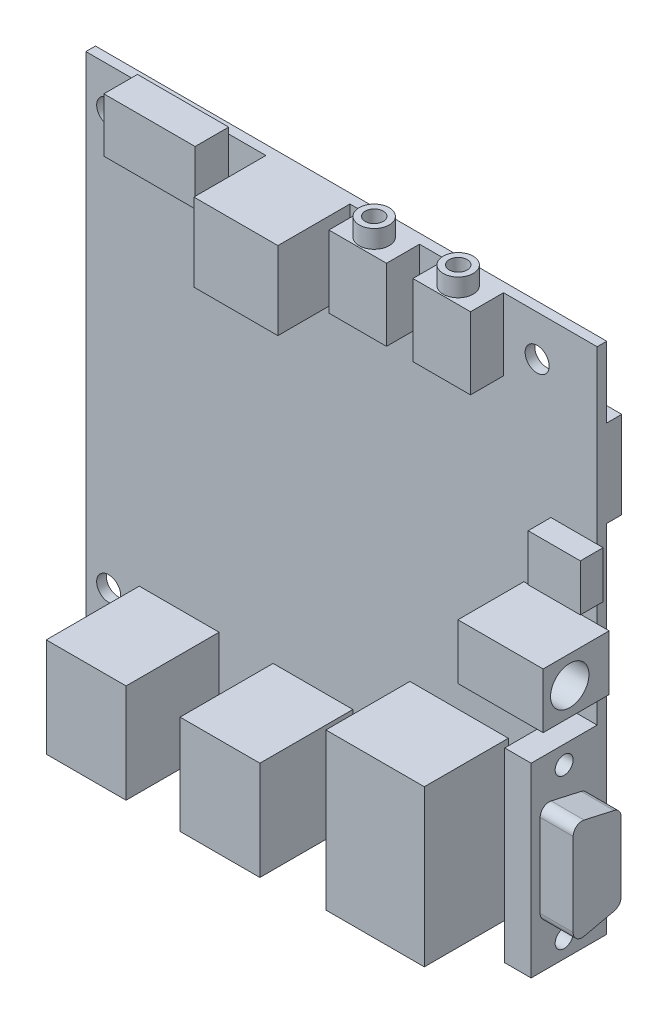
SolidWorks part; units mm, degrees
ref_plane "Piano frontale" through (0, 0, 0) normal (0, 0, 1) x (1, 0, 0)
ref_plane "Piano superiore" through (0, 0, 0) normal (0, 1, 0) x (1, 0, 0)
ref_plane "Piano destro" through (0, 0, 0) normal (1, 0, 0) x (0, 0, -1)
sketch "Schizzo1" plane through (0, 0, 0) normal (0, 0, 1) x (1, 0, 0)
  line L1 (42.6, -42.8) -> (-42.6, -42.8)
  line L2 (42.6, -42.8) -> (42.6, 42.8)
  line L3 (42.6, 42.8) -> (-42.6, 42.8)
  line L4 (-42.6, -42.8) -> (-42.6, 42.8)
  line L5 (42.6, -42.8) -> (-42.6, 42.8) construction
  line L6 (42.6, 42.8) -> (-42.6, -42.8) construction
  circle A0 centre (-38.8, 36) radius 2
  circle A1 centre (32.6, 36) radius 2
  circle A2 centre (-38.8, -32.8) radius 2
  circle A3 centre (32.6, -32.8) radius 2
  point P0 (0, 0)
  dimension "D5" = 4
  dimension "D6" = 4
  dimension "D9" = 4
  dimension "D12" = 4
  dimension "D1" = 85.2
  dimension "D2" = 85.6
  dimension "D3" = 6.8
  dimension "D4" = 3.8
  dimension "D7" = 10
  dimension "D8" = 6.8
  dimension "D10" = 10
  dimension "D11" = 3.8
  dimension "D13" = 10
  dimension "D14" = 10
extrude "Estrusione-Estrusione1" add sketch "Schizzo1" along normal blind 1.6
sketch "Schizzo2" plane through (0, 0, 1.6) normal (0, 0, 1) x (1, 0, 0)
  text T0 "beagleboard xm"
sketch "Schizzo3" plane through (0, 0, 1.6) normal (0, 0, 1) x (1, 0, 0)
  line L0 (-42.6, 42.8) -> (-42.6, -42.8) construction
  line L1 (-34, 43.8) -> (-18.8, 43.8)
  line L2 (-34, 43.8) -> (-34, 34.8)
  line L3 (-34, 34.8) -> (-18.8, 34.8)
  line L4 (-18.8, 43.8) -> (-18.8, 34.8)
  line L5 (42.6, 42.8) -> (-42.6, 42.8) construction
  dimension "D1" = 8.6
  dimension "D2" = 15.2
  dimension "D3" = 9
  dimension "D4" = 1
extrude "Estrusione-Estrusione2" add sketch "Schizzo3" along normal blind 5.6
sketch "Schizzo4" plane through (0, 0, 1.6) normal (0, 0, 1) x (1, 0, 0)
  line L0 (42.6, 42.8) -> (-18.8, 42.8) construction
  line L1 (-12.6, 42.8) -> (1.4, 42.8)
  line L2 (-12.6, 42.8) -> (-12.6, 29.8)
  line L3 (-12.6, 29.8) -> (1.4, 29.8)
  line L4 (1.4, 42.8) -> (1.4, 29.8)
  line L5 (-42.6, 42.8) -> (-42.6, -42.8) construction
  dimension "D1" = 30
  dimension "D2" = 14
  dimension "D3" = 13
extrude "Estrusione-Estrusione3" add sketch "Schizzo4" along normal blind 12
sketch "Schizzo5" plane through (0, 0, 1.6) normal (0, 0, 1) x (1, 0, 0)
  line L0 (42.6, 42.8) -> (1.4, 42.8) construction
  line L1 (3.4, 42.8) -> (13, 42.8)
  line L2 (3.4, 42.8) -> (3.4, 30.8)
  line L3 (3.4, 30.8) -> (13, 30.8)
  line L4 (13, 42.8) -> (13, 30.8)
  line L5 (-42.6, 42.8) -> (-42.6, -42.8) construction
  line L6 (17.4, 42.8) -> (27, 42.8)
  line L7 (17.4, 42.8) -> (17.4, 30.8)
  line L8 (17.4, 30.8) -> (27, 30.8)
  line L9 (27, 42.8) -> (27, 30.8)
  dimension "D1" = 46
  dimension "D2" = 9.6
  dimension "D3" = 9.6
  dimension "D4" = 60
  dimension "D5" = 12
  dimension "D6" = 12
extrude "Estrusione-Estrusione4" add sketch "Schizzo5" along normal blind 5.5
sketch "Schizzo6" plane through (0, 42.8, 0) normal (0, 1, 0) x (1, 0, 0)
  line L0 (3.4, -7.1) -> (3.4, -1.6) construction
  line L1 (3.4, -4.35) -> (27, -4.35) construction
  line L2 (27, -7.1) -> (27, -1.6) construction
  circle A0 centre (8.2, -4.35) radius 2.5
  circle A1 centre (22.2, -4.35) radius 2.5
  point P2 (3.4, -4.35)
  dimension "D1" = 5
  dimension "D2" = 5
extrude "Estrusione-Sottile1" add sketch "Schizzo6" along normal blind 3 thin thin type one direction reverse wall 1
sketch "Schizzo7" plane through (0, 0, 0) normal (0, 0, -1) x (-1, 0, 0)
  line L0 (-42.6, -42.8) -> (-42.6, 42.8) construction
  line L1 (-42.6, 31) -> (-26.6, 31)
  line L2 (-42.6, 31) -> (-42.6, 16.5)
  line L3 (-42.6, 16.5) -> (-26.6, 16.5)
  line L4 (-26.6, 31) -> (-26.6, 16.5)
  line L5 (-42.6, 42.8) -> (42.6, 42.8) construction
  dimension "D1" = 11.8
  dimension "D2" = 14.5
  dimension "D3" = 16
extrude "Estrusione-Estrusione5" add sketch "Schizzo7" along normal blind 2.5
sketch "Schizzo8" plane through (0, 0, 1.6) normal (0, 0, 1) x (1, 0, 0)
  line L1 (43.6, 14.3) -> (34.9, 14.3)
  line L2 (43.6, 14.3) -> (43.6, 6.5)
  line L3 (43.6, 6.5) -> (34.9, 6.5)
  line L4 (34.9, 14.3) -> (34.9, 6.5)
  line L5 (42.6, 42.8) -> (27, 42.8) construction
  line L6 (42.6, 31) -> (42.6, 42.8) construction
  point P4 (42.6, 36.9)
  dimension "D1" = 28.5
  dimension "D2" = 7.8
  dimension "D3" = 8.7
  dimension "D4" = 1
extrude "Estrusione-Estrusione6" add sketch "Schizzo8" along normal blind 3.8
sketch "Schizzo9" plane through (0, 0, 1.6) normal (0, 0, 1) x (1, 0, 0)
  line L1 (44.6, 2.8) -> (30.4, 2.8)
  line L2 (44.6, 2.8) -> (44.6, -6.4)
  line L3 (44.6, -6.4) -> (30.4, -6.4)
  line L4 (30.4, 2.8) -> (30.4, -6.4)
  line L5 (42.6, 42.8) -> (27, 42.8) construction
  line L6 (42.6, 14.3) -> (42.6, 42.8) construction
  dimension "D1" = 40
  dimension "D2" = 9.2
  dimension "D3" = 2
  dimension "D4" = 14.2
extrude "Estrusione-Estrusione7" add sketch "Schizzo9" along normal blind 11
sketch "Schizzo10" plane through (44.6, 0, 0) normal (1, 0, 0) x (0, 0, -1)
  circle A0 centre (-8.1632, -1.8) radius 3.2
  dimension "D1" = 6.4
extrude "Taglio-Estrusione1" cut sketch "Schizzo10" against normal blind 10
sketch "Schizzo11" plane through (0, 0, 1.6) normal (0, 0, 1) x (1, 0, 0)
  line L1 (42.6, -42.8) -> (38.2, -42.8)
  line L2 (42.6, -42.8) -> (42.6, -11.8)
  line L3 (42.6, -11.8) -> (38.2, -11.8)
  line L4 (38.2, -42.8) -> (38.2, -11.8)
  dimension "D1" = 31
  dimension "D2" = 4.4
extrude "Estrusione-Estrusione8" add sketch "Schizzo11" along normal blind 11
sketch "Schizzo12" plane through (42.6, 0, 0) normal (1, 0, 0) x (0, 0, -1)
  line L0 (-7.1, -11.8) -> (-7.1, -42.8) construction
  line L1 (-12.6, -11.8) -> (-1.6, -11.8) construction
  line L2 (-12.6, -42.8) -> (0, -42.8) construction
  line L3 (-11.1, -34.225) -> (-11.1, -20.375)
  line L4 (-3.1, -33.1) -> (-3.1, -21.5)
  line L5 (-9.2707, -18.9116) -> (-4.2707, -20.0366)
  line L6 (-9.2707, -35.6884) -> (-4.2707, -34.5634)
  line L7 (-12.6, -27.3) -> (0, -27.3) construction
  line L8 (-12.6, -42.8) -> (-12.6, -11.8) construction
  line L9 (0, -42.8) -> (0, 16.5) construction
  arc A0 (-3.1, -21.5) -> (-4.2707, -20.0366) centre (-4.6, -21.5) ccw
  arc A1 (-9.2707, -18.9116) -> (-11.1, -20.375) centre (-9.6, -20.375) ccw
  arc A2 (-3.1, -33.1) -> (-4.2707, -34.5634) centre (-4.6, -33.1) cw
  arc A3 (-9.2707, -35.6884) -> (-11.1, -34.225) centre (-9.6, -34.225) cw
  point P18 (-3.1, -20.3)
  point P21 (-11.1, -18.5)
  point P26 (-3.1, -27.3)
  point P28 (-11.1, -27.3)
  dimension "D1" = 8.8
  dimension "D3" = 1.5
  dimension "D2" = 7
  dimension "D4" = 4
  dimension "D5" = 4
extrude "Estrusione-Estrusione9" add sketch "Schizzo12" along normal blind 5.5
sketch "Schizzo14" plane through (42.6, 0, 0) normal (1, 0, 0) x (0, 0, -1)
  line L0 (-12.6, -11.8) -> (-1.6, -11.8) construction
  line L1 (-12.6, -42.8) -> (0, -42.8) construction
  circle A0 centre (-7.1, -14.8) radius 1.5
  circle A1 centre (-7.1, -39.8) radius 1.5
  point P4 (-7.1, -11.8)
  dimension "D3" = 3
  dimension "D4" = 3
  dimension "D1" = 3
  dimension "D2" = 3
extrude "Taglio-Estrusione2" cut sketch "Schizzo14" against normal blind 5.5
sketch "Schizzo15" plane through (0, 0, 1.6) normal (0, 0, 1) x (1, 0, 0)
  line L1 (27.8, -47.1) -> (11.4, -47.1)
  line L2 (27.8, -47.1) -> (27.8, -21.1)
  line L3 (27.8, -21.1) -> (11.4, -21.1)
  line L4 (11.4, -47.1) -> (11.4, -21.1)
  line L5 (42.6, -42.8) -> (42.6, -11.8) construction
  line L6 (-42.6, -42.8) -> (38.2, -42.8) construction
  dimension "D1" = 14.8
  dimension "D2" = 16.4
  dimension "D3" = 4.3
  dimension "D4" = 26
extrude "Estrusione-Estrusione10" add sketch "Schizzo15" along normal blind 14
sketch "Schizzo16" plane through (0, 0, 1.6) normal (0, 0, 1) x (1, 0, 0)
  line L0 (-42.6, 42.8) -> (-42.6, -42.8) construction
  line L1 (-33.7, -46.4) -> (-20.4, -46.4)
  line L2 (-33.7, -46.4) -> (-33.7, -29.9)
  line L3 (-33.7, -29.9) -> (-20.4, -29.9)
  line L4 (-20.4, -46.4) -> (-20.4, -29.9)
  line L5 (-42.6, -42.8) -> (11.4, -42.8) construction
  line L6 (-11.4, -46.4) -> (1.9, -46.4)
  line L7 (-11.4, -46.4) -> (-11.4, -29.9)
  line L8 (-11.4, -29.9) -> (1.9, -29.9)
  line L9 (1.9, -46.4) -> (1.9, -29.9)
  dimension "D1" = 8.9
  dimension "D2" = 3.6
  dimension "D3" = 13.3
  dimension "D4" = 16.5
extrude "Estrusione-Estrusione11" add sketch "Schizzo16" along normal blind 15.5
sketch "Schizzo17" plane through (0, 0, 0) normal (0, 0, -1) x (-1, 0, 0)
  line L0 (-42.6, 42.8) -> (42.6, 42.8) construction
  line L1 (40.2, 24.5) -> (32.9, 24.5)
  line L2 (40.2, 24.5) -> (40.2, 11.5)
  line L3 (40.2, 11.5) -> (32.9, 11.5)
  line L4 (32.9, 24.5) -> (32.9, 11.5)
  line L5 (39.4, 8.8) -> (34.4, 8.8)
  line L6 (39.4, 8.8) -> (39.4, -26.8)
  line L7 (39.4, -26.8) -> (34.4, -26.8)
  line L8 (34.4, 8.8) -> (34.4, -26.8)
  line L9 (42.6, 42.8) -> (42.6, -42.8) construction
  line L10 (42.6, -42.8) -> (-42.6, -42.8) construction
  dimension "D1" = 13
  dimension "D2" = 7.3
  dimension "D3" = 18.3
  dimension "D4" = 2.4
  dimension "D5" = 35.6
  dimension "D6" = 5
  dimension "D7" = 16
  dimension "D8" = 3.2
extrude "Estrusione-Estrusione12" add sketch "Schizzo17" along normal blind 3.9
